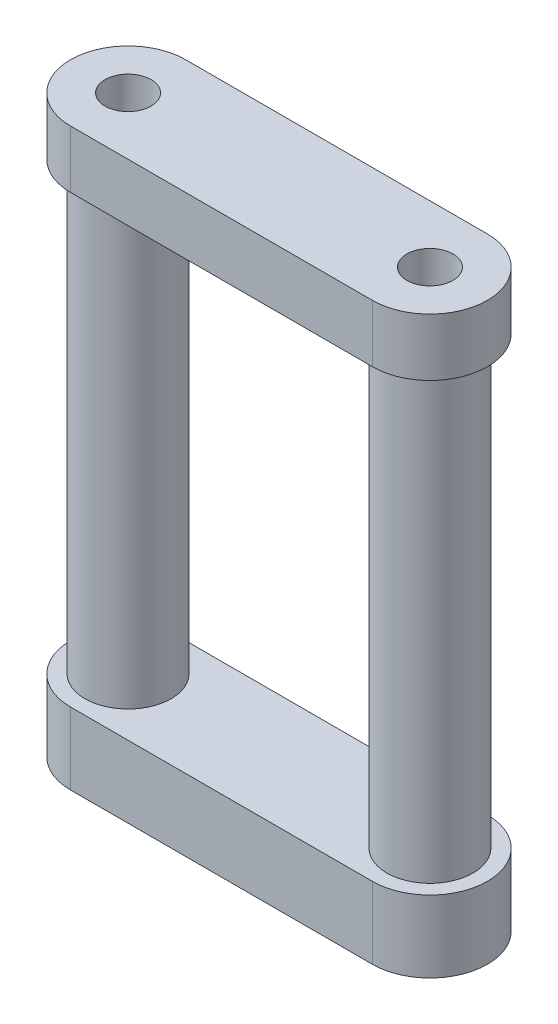
SolidWorks part; units mm, degrees
ref_plane "正面" through (0, 0, 0) normal (0, 0, 1) x (1, 0, 0)
ref_plane "平面" through (0, 0, 0) normal (0, 1, 0) x (1, 0, 0)
ref_plane "右側面" through (0, 0, 0) normal (1, 0, 0) x (0, 0, -1)
sketch "ｽｹｯﾁ1" plane through (0, 0, 0) normal (0, 1, 0) x (1, 0, 0)
  line L0 (-10.5, 0) -> (10.5, 0) construction
  line L1 (-10.5, 4) -> (10.5, 4)
  line L2 (-10.5, -4) -> (10.5, -4)
  arc A0 (-10.5, 4) -> (-10.5, -4) centre (-10.5, 0) ccw
  arc A1 (10.5, -4) -> (10.5, 4) centre (10.5, 0) ccw
  circle A2 centre (-10.5, 0) radius 1.5
  circle A3 centre (10.5, 0) radius 1.5
  point P2 (0, 0)
  dimension "D2" = 3
  dimension "D3" = 4
  dimension "D1" = 21
extrude "ﾎﾞｽ - 押し出し1" add sketch "ｽｹｯﾁ1" along normal blind 5
sketch "ｽｹｯﾁ2" plane through (0, 5, 0) normal (0, 1, 0) x (1, 0, 0)
  circle A0 centre (-10.5, 0) radius 3
  circle A1 centre (-10.5, 0) radius 1.6
  circle A2 centre (10.5, 0) radius 1.6
  circle A3 centre (10.5, 0) radius 3
  dimension "D1" = 3.2
  dimension "D2" = 6
extrude "ﾎﾞｽ - 押し出し2" add sketch "ｽｹｯﾁ2" along normal blind 31 separate body
sketch "ｽｹｯﾁ3" plane through (0, 36, 0) normal (0, 1, 0) x (1, 0, 0)
  line L2 (-10.5, -4) -> (10.5, -4)
  line L3 (10.5, 4) -> (-10.5, 4)
  line L4 (-10.5, -4) -> (10.5, -4)
  line L5 (10.5, 4) -> (-10.5, 4)
  circle A0 centre (10.5, 0) radius 1.6 construction
  circle A1 centre (-10.5, 0) radius 1.6 construction
  arc A2 (-10.5, 4) -> (-10.5, -4) centre (-10.5, 0) ccw
  arc A3 (10.5, -4) -> (10.5, 4) centre (10.5, 0) ccw
  arc A4 (-10.5, 4) -> (-10.5, -4) centre (-10.5, 0) ccw
  arc A5 (10.5, -4) -> (10.5, 4) centre (10.5, 0) ccw
  circle A6 centre (10.5, 0) radius 1.6
  circle A7 centre (-10.5, 0) radius 1.6
  dimension "D1" = 0
extrude "ﾎﾞｽ - 押し出し3" add sketch "ｽｹｯﾁ3" along normal blind 4 separate body
